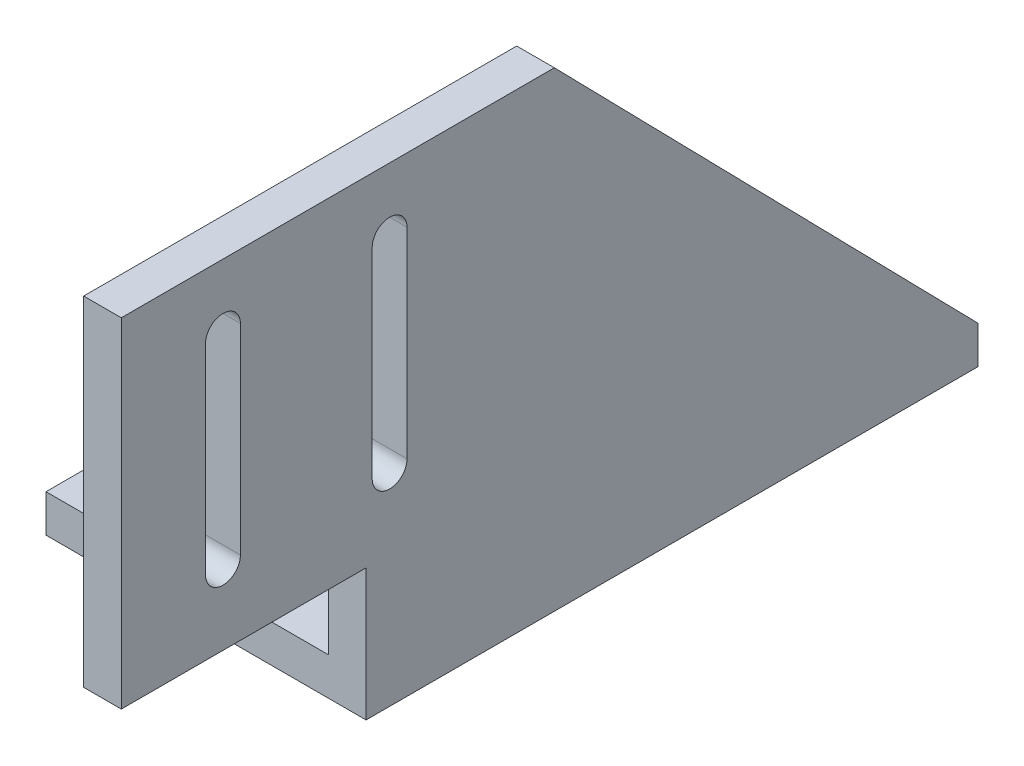
SolidWorks part; units mm, degrees
ref_plane "Front Plane" through (0, 0, 0) normal (1, 0, 0) x (0, 1, 0)
ref_plane "Top Plane" through (0, 0, 0) normal (0, 0, 1) x (0, 1, 0)
ref_plane "Right Plane" through (0, 0, 0) normal (0, 1, 0) x (-1, 0, 0)
sketch "Sketch1" plane through (0, 0, 0) normal (0, 0, 1) x (0, 1, 0)
  line L0 (0, 0) -> (0, -15)
  line L1 (0, -15) -> (23, -15)
  line L2 (23, -15) -> (23, -17)
  line L3 (23, -17) -> (-2, -17)
  line L4 (-2, -17) -> (-2, 0)
  line L5 (-2, 0) -> (0, 0)
  dimension "D1" = 15
  dimension "D2" = 2
  dimension "D3" = 25
extrude "Boss-Extrude1" add sketch "Sketch1" along normal blind 32.5
sketch "Sketch2" plane through (0, -2, 0) normal (0, -1, 0) x (1, 0, 0)
  line L0 (0, 16.25) -> (17, 16.25) construction
  line L1 (0, 32.5) -> (0, 0) construction
  line L2 (17, 32.5) -> (17, 0) construction
  circle A0 centre (8, 25.25) radius 2.75
  circle A1 centre (8, 7.25) radius 2.75
  dimension "D1" = 5.5
  dimension "D2" = 18
  dimension "D3" = 8
extrude "Cut-Extrude1" cut sketch "Sketch2" against normal up to surface (2 mm away) up to face at (7.5, 0, 16.25)
sketch "Sketch3" plane through (17, 0, 0) normal (1, 0, 0) x (0, 1, 0)
  line L0 (23, 22.5) -> (0, 0)
  line L7 (23, 32.5) -> (23, 0) construction
  line L8 (23, 22.5) -> (23, 0)
  line L9 (23, 0) -> (0, 0)
  point P0 (0, 0)
  dimension "D1" = 10
extrude "Cut-Extrude2" cut sketch "Sketch3" against normal blind 2
sketch "Sketch4" plane through (17, 0, 0) normal (1, 0, 0) x (0, 1, 0)
  line L0 (23, 32.5) -> (23, 22.5) construction
  line L1 (-2, 32.5) -> (23, 32.5)
  line L2 (-2, 32.5) -> (-2, 45.5)
  line L3 (-2, 45.5) -> (23, 45.5)
  line L4 (23, 32.5) -> (23, 45.5)
  dimension "D1" = 13
extrude "Boss-Extrude2" add sketch "Sketch4" against normal blind 2
sketch "Sketch5" plane through (17, 0, 0) normal (1, 0, 0) x (0, 1, 0)
  line L0 (8.925, 40.1) -> (19.575, 40.1) construction
  line L3 (8.925, 41.025) -> (19.575, 41.025)
  line L4 (8.925, 39.175) -> (19.575, 39.175)
  line L5 (8.925, 31.25) -> (19.575, 31.25) construction
  line L6 (8.925, 32.175) -> (19.575, 32.175)
  line L7 (8.925, 30.325) -> (19.575, 30.325)
  line L8 (23, 45.5) -> (-2, 45.5) construction
  line L11 (23, 45.5) -> (23, 22.5) construction
  line L15 (-2, 45.5) -> (-2, 0) construction
  arc A2 (8.925, 41.025) -> (8.925, 39.175) centre (8.925, 40.1) ccw
  arc A3 (19.575, 39.175) -> (19.575, 41.025) centre (19.575, 40.1) ccw
  arc A4 (8.925, 32.175) -> (8.925, 30.325) centre (8.925, 31.25) ccw
  arc A5 (19.575, 30.325) -> (19.575, 32.175) centre (19.575, 31.25) ccw
  point P4 (14.25, 40.1)
  point P15 (14.25, 31.25)
  point P22 (0, 0)
  dimension "D1" = 7
  dimension "D2" = 5.4
  dimension "D3" = 2.5
  dimension "D4" = 10
  dimension "D5" = 1.85
extrude "Cut-Extrude3" cut sketch "Sketch5" against normal up to next
sketch "Sketch7" plane through (17, 0, 0) normal (1, 0, 0) x (0, 1, 0)
  line L8 (-2, 45.5) -> (5, 45.5)
  line L9 (-2, 45.5) -> (-2, 32.5)
  line L10 (-2, 32.5) -> (5, 32.5)
  line L11 (5, 45.5) -> (5, 32.5)
  dimension "D1" = 7
  dimension "D2" = 13
extrude "Cut-Extrude4" cut sketch "Sketch7" against normal up to next
